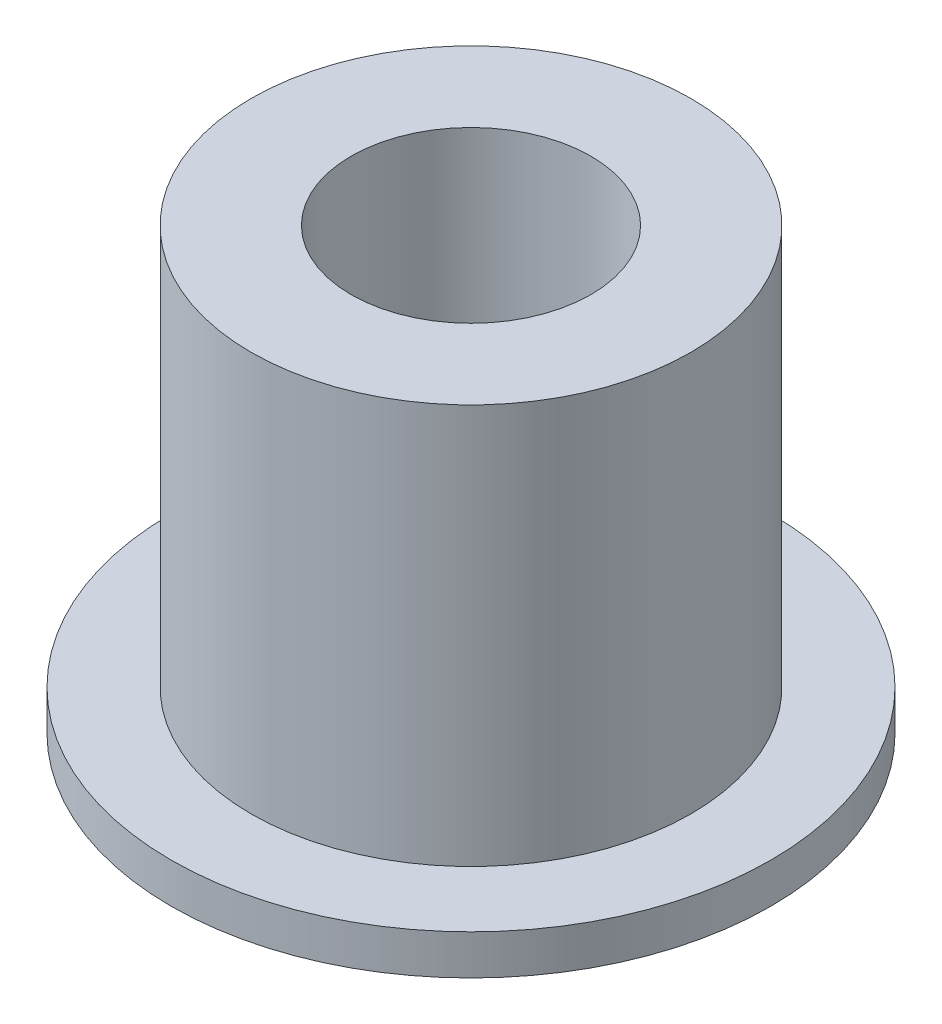
SolidWorks part; units mm, degrees
ref_plane "Front Plane" through (0, 0, 0) normal (0, 0, 1) x (1, 0, 0)
ref_plane "Top Plane" through (0, 0, 0) normal (0, 1, 0) x (1, 0, 0)
ref_plane "Right Plane" through (0, 0, 0) normal (1, 0, 0) x (0, 0, -1)
sketch "Sketch1" plane through (0, 0, 0) normal (0, 1, 0) x (1, 0, 0)
  circle A0 centre (0, 0) radius 5.5
  dimension "D1" = 11
extrude "Boss-Extrude1" add sketch "Sketch1" along normal mid plane 11
sketch "Sketch2" plane through (0, -5.5, 0) normal (0, -1, 0) x (1, 0, 0)
  circle A0 centre (0, 0) radius 7.5
  dimension "D1" = 15
extrude "Boss-Extrude2" add sketch "Sketch2" against normal blind 1
sketch "Sketch3" plane through (0, 5.5, 0) normal (0, 1, 0) x (1, 0, 0)
  circle A0 centre (0, 0) radius 3
  dimension "D1" = 6
extrude "Cut-Extrude1" cut sketch "Sketch3" against normal through all
